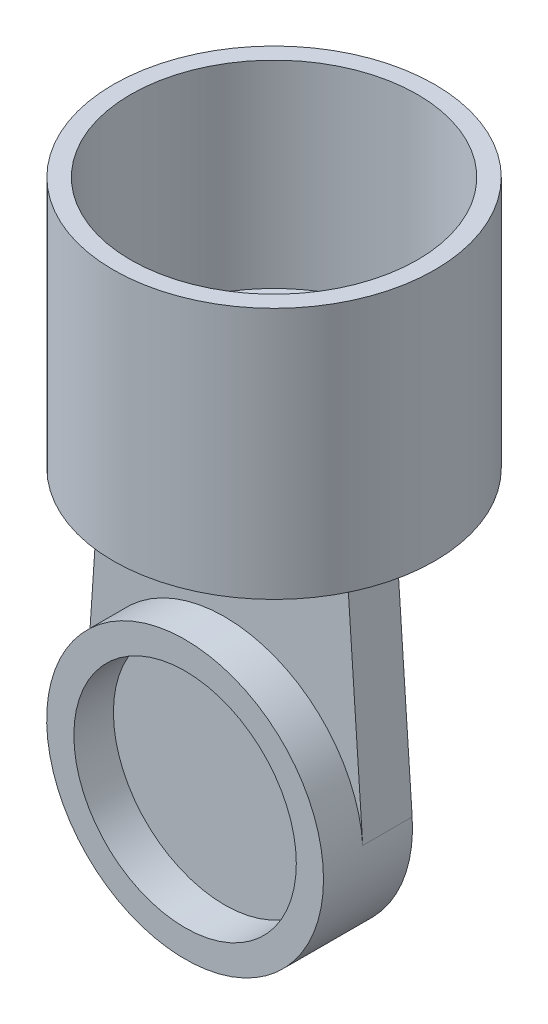
SolidWorks part; units mm, degrees
ref_plane "前视基准面" through (0, 0, 0) normal (0, 0, 1) x (1, 0, 0)
ref_plane "上视基准面" through (0, 0, 0) normal (0, 1, 0) x (1, 0, 0)
ref_plane "右视基准面" through (0, 0, 0) normal (1, 0, 0) x (0, 0, -1)
other "Configuration Table"
sketch "草图1" plane through (0, 0, 0) normal (0, 0, 1) x (1, 0, 0)
  line L0 (0, 0) -> (0, 60) construction
  line L1 (0, 60) -> (-24, 60)
  line L2 (-24, 60) -> (-27.936, 1.8923)
  line L3 (0, 60) -> (24, 60)
  line L4 (24, 60) -> (27.936, 1.8923)
  arc A0 (-27.936, 1.8923) -> (27.936, 1.8923) centre (0, 0) ccw
  dimension "D1" = 56
  dimension "D2" = 24
  dimension "D3" = 24
  dimension "D4" = 60
extrude "凸台-拉伸1" add sketch "草图1" along normal blind 10
sketch "草图2" plane through (0, 0, 10) normal (0, 0, 1) x (1, 0, 0)
  circle A0 centre (0, 0) radius 28
  circle A1 centre (0, 0) radius 22.5
  dimension "D1" = 45
extrude "凸台-拉伸2" add sketch "草图2" along normal blind 8
sketch "草图3" plane through (0, 60, 0) normal (0, 1, 0) x (1, 0, 0)
  circle A0 centre (0, 0) radius 29
  circle A1 centre (0, 0) radius 32.5
  dimension "D1" = 58
  dimension "D2" = 65
extrude "凸台-拉伸3" add sketch "草图3" along normal blind 40
sketch "草图4" plane through (0, 60, 0) normal (0, -1, 0) x (1, 0, 0)
  circle A0 centre (0, 0) radius 32.5
extrude "凸台-拉伸4" add sketch "草图4" along normal blind 11
sketch "草图5" plane through (0, 0, 0) normal (1, 0, 0) x (0, 0, -1)
  line L0 (0, -15.7901) -> (23.9981, 49)
  line L2 (0, -28) -> (0, 1.8923) construction
  line L3 (-32.5, 49) -> (32.5, 49) construction
rib "筋4" sketch "草图5" sketch "草图5" thickness 8 extrusion direction parallel to sketch draft on no parameters "D1"=8
sketch "草图6" plane through (0, 60, 0) normal (0, 1, 0) x (1, 0, 0)
  line L1 (-12.0073, -25.8516) -> (12.0073, -25.8516)
  line L2 (-12.0073, -25.8516) -> (-12.0073, -16.7117)
  line L3 (-12.0073, -16.7117) -> (12.0073, -16.7117)
  line L4 (12.0073, -25.8516) -> (12.0073, -16.7117)
  line L5 (-12.0073, -25.8516) -> (12.0073, -16.7117) construction
  line L6 (-12.0073, -16.7117) -> (12.0073, -25.8516) construction
  point P0 (0, -21.2817)
extrude "切除-拉伸1" cut sketch "草图6" against normal blind 16
